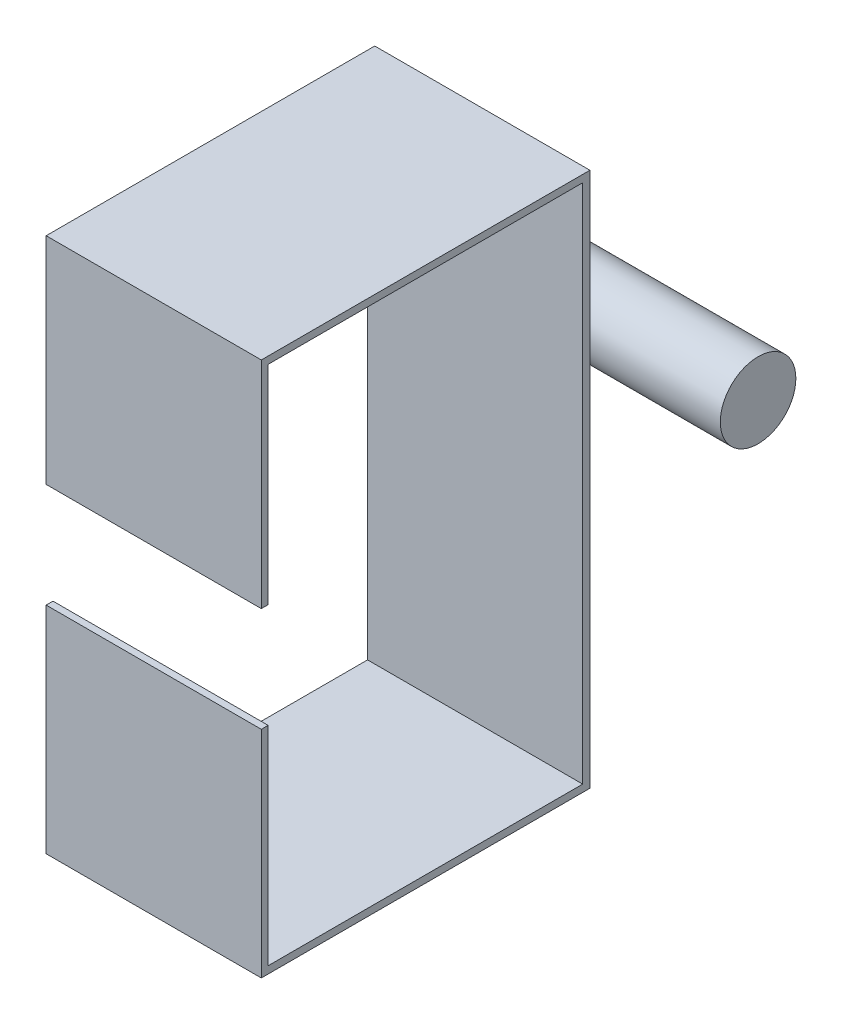
SolidWorks part; units mm, degrees
material "6061-T6 (SS)"
ref_plane "Front Plane" through (0, 0, 0) normal (1, 0, 0) x (0, 1, 0)
ref_plane "Top Plane" through (0, 0, 0) normal (0, 0, 1) x (0, 1, 0)
ref_plane "Right Plane" through (0, 0, 0) normal (0, 1, 0) x (-1, 0, 0)
sketch "Sketch1" plane through (0, 0, 0) normal (1, 0, 0) x (0, 1, 0)
  line L0 (-32.3952, 0) -> (32.3952, 0)
  line L1 (32.3952, 0) -> (32.3952, 39.7764)
  line L2 (32.3952, 39.7764) -> (6.3246, 39.7764)
  line L3 (6.3246, 39.7764) -> (6.3246, 38.9484)
  line L4 (6.3246, 38.9484) -> (31.5214, 38.9484)
  line L5 (31.5214, 38.9484) -> (31.5214, 0.8738)
  line L6 (31.5214, 0.8738) -> (-31.5214, 0.8738)
  line L7 (-31.5214, 0.8738) -> (-31.5214, 38.9484)
  line L8 (-31.5214, 38.9484) -> (-6.3246, 38.9484)
  line L9 (-6.3246, 38.9484) -> (-6.3246, 39.7764)
  line L10 (-6.3246, 39.7764) -> (-32.3952, 39.7764)
  line L11 (-32.3952, 39.7764) -> (-32.3952, 0)
  point P3 (0, 0)
  dimension "D1" = 0.8738
  dimension "D2" = 0.8738
  dimension "D3" = 0.8738
  dimension "D4" = 38.0746
  dimension "D6" = 63.0428
  dimension "D7" = 0.828
  dimension "D8" = 0.828
  dimension "D5" = 38.0746
  dimension "D9" = 25.1968
  dimension "D10" = 25.1968
extrude "Boss-Extrude1" add sketch "Sketch1" along normal blind 26.0452
sketch "Sketch2" plane through (0, 0, 0) normal (1, 0, 0) x (0, 1, 0)
  line L0 (-4.5339, 0) -> (4.5339, 0)
  line L1 (-32.3952, 0) -> (32.3952, 0) construction
  line L2 (4.5339, 0) -> (4.5339, -19.05)
  line L4 (-4.5339, -19.05) -> (-4.5339, 0)
  arc A0 (-4.5339, -19.05) -> (4.5339, -19.05) centre (0, -18.461) ccw
  dimension "D2" = 4.572
  dimension "D1" = 9.0678
  dimension "D3" = 19.05
extrude "Boss-Extrude2" add sketch "Sketch2" along normal blind 2.54
sketch "Sketch5" plane through (0, 0, 0) normal (1, 0, 0) x (0, 1, 0)
  circle A0 centre (0, -18.461) radius 4.572
  arc A1 (-4.5339, -19.05) -> (4.5339, -19.05) centre (0, -18.461) ccw construction
extrude "Boss-Extrude3" add sketch "Sketch5" along normal blind 27.94
equation "\"a\"= 0.498"
equation "\"b\"= 0.992"
equation "\"c\"= 1.499"
equation "\"Overall Width\"= \"a\" + \"b\" + \"b\""
equation "\"Pin Diameter\"= .357"
equation "\"Hangar Width\"= .357"
equation "\"Wall Width\"= 0.0344"
equation "\"Pin Length\"= 1"
equation "\"Flange Width\"=0.0326"
equation "\"Flange Length\"= 600 / ( 2 * .36 * 9000 )"
equation "\"Pin To Base\"= 0.75"
equation "\"Flange Height\"= .0334"
equation "\"D1@Sketch1\"=\"Wall Width\""
equation "\"D2@Sketch1\"=\"Wall Width\""
equation "\"D3@Sketch1\"=\"Wall Width\""
equation "\"D4@Sketch1\"=\"c\""
equation "\"D6@Sketch1\"=\"Overall Width\""
equation "\"D5@Sketch1\"=\"c\""
equation "\"D8@Sketch1\"=\"Flange Width\""
equation "\"D7@Sketch1\"=\"Flange Width\""
equation "\"D10@Sketch1\"=\"b\""
equation "\"D9@Sketch1\"=\"b\""
equation "\"Bracket Width\"= \"b\" + \"Flange Height\""
equation "\"D1@Boss-Extrude1\"=\"Bracket Width\""
equation "\"D1@Sketch2\"=\"Pin Diameter\""
equation "\"D2@Sketch2\"=.36/2"
equation "\"D3@Sketch2\"=\"Pin To Base\""
